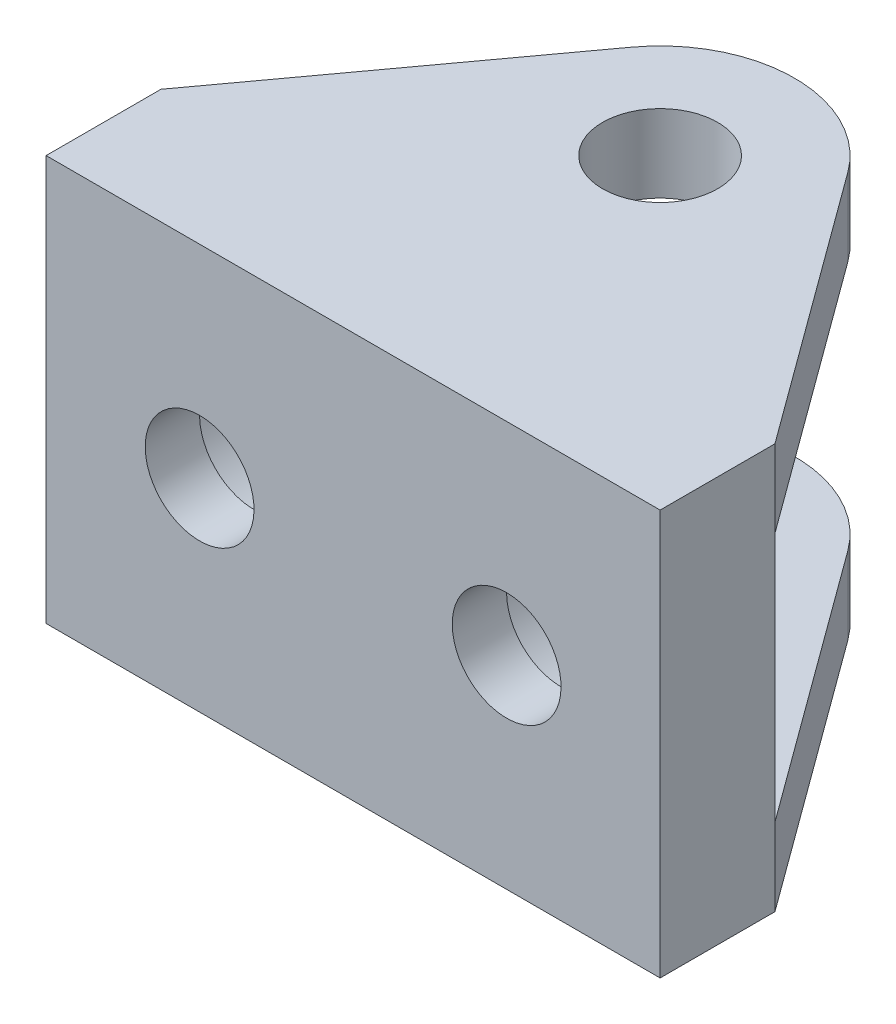
SolidWorks part; units mm, degrees
ref_plane "Front Plane" through (0, 0, 0) normal (0, 0, 1) x (1, 0, 0)
ref_plane "Top Plane" through (0, 0, 0) normal (0, 1, 0) x (1, 0, 0)
ref_plane "Right Plane" through (0, 0, 0) normal (1, 0, 0) x (0, 0, -1)
sketch "Sketch1" plane through (0, 0, 0) normal (0, 1, 0) x (1, 0, 0)
  line L0 (0, 0) -> (50.8, 0)
  line L1 (50.8, 0) -> (50.8, 9.4996)
  line L2 (0, 0) -> (0, 9.4996)
  line L3 (50.8, 9.4996) -> (34.3689, 31.961)
  line L4 (0, 9.4996) -> (16.4311, 31.961)
  line L5 (25.4, 0) -> (25.4, 43.8119) construction
  circle A0 centre (25.4, 25.4) radius 4.7625
  arc A1 (34.3689, 31.961) -> (16.4311, 31.961) centre (25.4, 25.4) ccw
  dimension "D4" = 6.35
  dimension "D5" = 9.525
  dimension "D1" = 25.4
  dimension "D2" = 50.8
  dimension "D3" = 9.4996
extrude "Boss-Extrude1" add sketch "Sketch1" along normal blind 33.528
sketch "Sketch2" plane through (50.8, 0, 0) normal (1, 0, 0) x (0, 0, -1)
  line L0 (9.4996, 16.764) -> (9.4996, 27.1145)
  line L1 (9.4996, 33.528) -> (9.4996, 0) construction
  line L2 (9.4996, 27.1145) -> (36.5125, 27.1145)
  line L3 (9.4996, 16.764) -> (9.4996, 6.4135)
  line L4 (9.4996, 6.4135) -> (36.5125, 6.4135)
  line L5 (36.5125, 6.4135) -> (36.5125, 27.1145)
  line L6 (36.5125, 0) -> (36.5125, 33.528) construction
  dimension "D1" = 20.701
extrude "Cut-Extrude1" cut sketch "Sketch2" against normal through all
sketch "Sketch3" plane through (0, 0, -9.4996) normal (0, 0, -1) x (-1, 0, 0)
  line L0 (-50.8, 16.764) -> (0, 16.764) construction
  line L1 (-50.8, 27.1145) -> (-50.8, 6.4135) construction
  line L2 (0, 27.1145) -> (0, 6.4135) construction
  line L3 (-25.4, 16.764) -> (-25.4, 27.1145) construction
  line L4 (0, 27.1145) -> (-50.8, 27.1145) construction
  point P10 (-38.1, 16.764)
  point P11 (-12.7, 16.764)
  dimension "D1" = 12.7
  dimension "D2" = 25.4
hole_wizard "CBORE for M8 Hex Head Bolt1" positions "Sketch3" profile "Sketch4" counterbore size "M8" standard "ANSI Metric" end condition through all
sketch "Sketch4" plane through (12.7, 16.764, -9.4996) normal (1, 0, 0) x (0, 1, 0)
  line L0 (0, 0) -> (0, 9.4996)
  line L1 (0, 9.4996) -> (4.5, 9.4996)
  line L3 (4.5, 9.4996) -> (4.5, 5)
  line L4 (4.5, 5) -> (8, 5)
  line L5 (8, 5) -> (8, 0)
  line L7 (8, 0) -> (0, 0)
  line L11 (0, -6.35) -> (0, 107.95) construction
  dimension "Thru Hole Dia." = 9
  dimension "Thru Hole Depth" = 9.4996
  dimension "C'Bore Dia." = 16
  dimension "C'Bore Depth" = 5
equation "\"1inch\"=62.1211"
